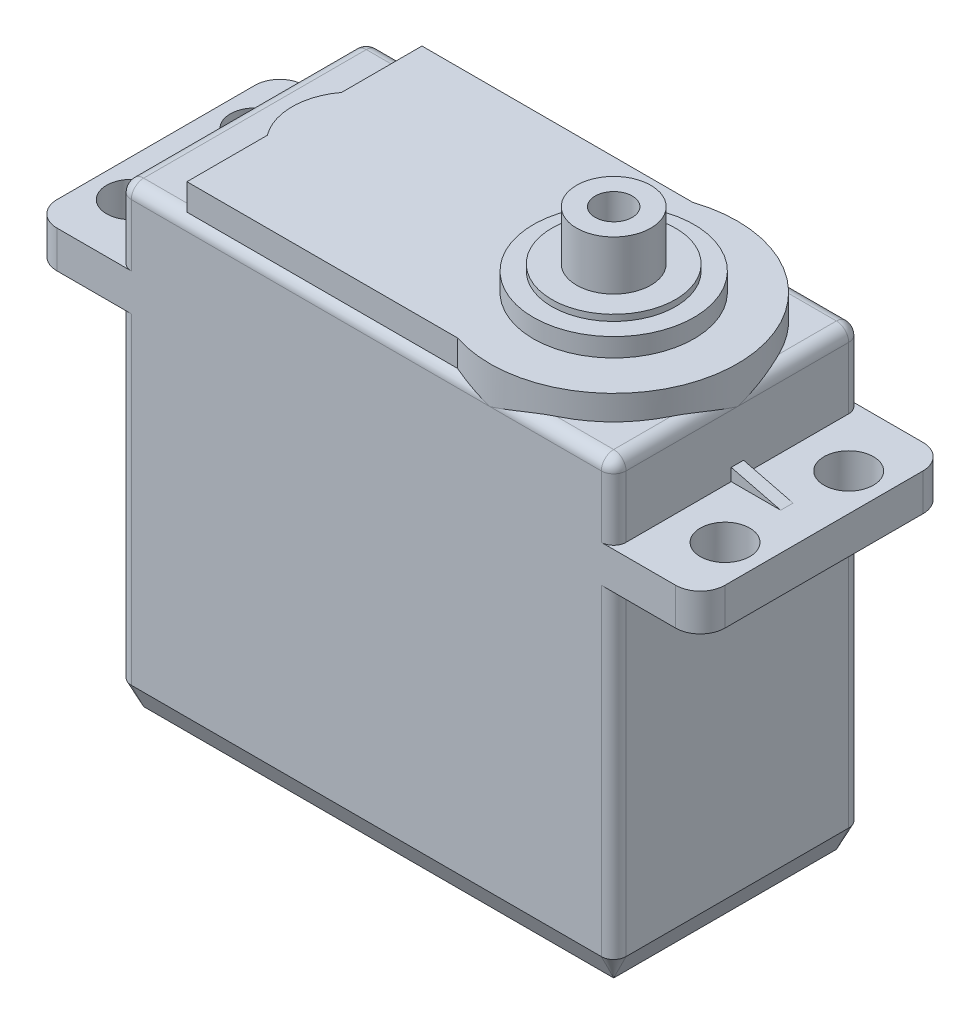
SolidWorks part; units mm, degrees
ref_plane "前视基准面" through (0, 0, 0) normal (0, 0, 1) x (1, 0, 0)
ref_plane "上视基准面" through (0, 0, 0) normal (0, 1, 0) x (1, 0, 0)
ref_plane "右视基准面" through (0, 0, 0) normal (1, 0, 0) x (0, 0, -1)
sketch "草图1" plane through (0, 0, 0) normal (0, 1, 0) x (1, 0, 0)
  line L1 (-27, 10) -> (27, 10)
  line L2 (-27, 10) -> (-27, -10)
  line L3 (-27, -10) -> (27, -10)
  line L4 (27, 10) -> (27, -10)
  line L5 (-27, 10) -> (27, -10) construction
  line L6 (-27, -10) -> (27, 10) construction
  point P0 (0, 0)
  dimension "D1" = 54
  dimension "D2" = 20
extrude "凸台-拉伸1" add sketch "草图1" along normal blind 37
sketch "草图2" plane through (0, 0, 0) normal (0, -1, 0) x (1, 0, 0)
  line L1 (-20, 10) -> (20, 10)
  line L2 (-20, 10) -> (-20, -10)
  line L3 (-20, -10) -> (20, -10)
  line L4 (20, 10) -> (20, -10)
  line L5 (-20, 10) -> (20, -10) construction
  line L6 (-20, -10) -> (20, 10) construction
  line L7 (-33.9613, 19.7038) -> (33.9613, 19.7038)
  line L8 (-33.9613, 19.7038) -> (-33.9613, -19.7038)
  line L9 (-33.9613, -19.7038) -> (33.9613, -19.7038)
  line L10 (33.9613, 19.7038) -> (33.9613, -19.7038)
  line L11 (-33.9613, 19.7038) -> (33.9613, -19.7038) construction
  line L12 (-33.9613, -19.7038) -> (33.9613, 19.7038) construction
  point P0 (0, 0)
  point P6 (0, 0)
  dimension "D1" = 40
  dimension "D2" = 20
extrude "切除-拉伸1" cut sketch "草图2" against normal blind 28
sketch "草图3" plane through (0, 37, 0) normal (0, 1, 0) x (1, 0, 0)
  line L1 (-20, 10) -> (20, 10)
  line L2 (-20, 10) -> (-20, -10)
  line L3 (-20, -10) -> (20, -10)
  line L4 (20, 10) -> (20, -10)
  line L5 (-20, 10) -> (20, -10) construction
  line L6 (-20, -10) -> (20, 10) construction
  line L7 (-33.9613, 16.6929) -> (33.9613, 16.6929)
  line L8 (-33.9613, 16.6929) -> (-33.9613, -16.6929)
  line L9 (-33.9613, -16.6929) -> (33.9613, -16.6929)
  line L10 (33.9613, 16.6929) -> (33.9613, -16.6929)
  line L11 (-33.9613, 16.6929) -> (33.9613, -16.6929) construction
  line L12 (-33.9613, -16.6929) -> (33.9613, 16.6929) construction
  point P0 (0, 0)
  point P6 (0, 0)
  dimension "D1" = 40
  dimension "D2" = 20
extrude "切除-拉伸2" cut sketch "草图3" against normal blind 6
fillet "圆角1" radius 1 12 edges at (20, 34, 10) (20, 34, -10) (-20, 34, 10) (-20, 34, -10) (-20, 14, -10) (20, 14, -10) (20, 14, 10) (-20, 14, 10) (20, 37, 0) (0, 37, -10) (-20, 37, 0) (0, 37, 10)
fillet "圆角2" radius 2 4 edges at (-27, 29.5, -10) (27, 29.5, -10) (-27, 29.5, 10) (27, 29.5, 10)
chamfer "倒角1" distance 1 distance2 2 8 edges at (0, 0, -10) (-19.7071, 0, -9.7071) (19.7071, 0, -9.7071) (-20, 0, 0) (20, 0, 0) (-19.7071, 0, 9.7071) (19.7071, 0, 9.7071) (0, 0, 10)
sketch "草图4" plane through (0, 37, 0) normal (0, 1, 0) x (1, 0, 0)
  line L0 (-36.3246, 0) -> (42.4452, 0) construction
  line L1 (0, 18.5837) -> (0, -20.5352) construction
  circle A0 centre (-24, 5) radius 2
  circle A1 centre (-24, -5) radius 2
  circle A2 centre (24, -5) radius 2
  circle A3 centre (24, 5) radius 2
  dimension "D4" = 4
  dimension "D5" = 4
  dimension "D1" = 5
  dimension "D2" = 5
  dimension "D3" = 24
extrude "切除-拉伸3" cut sketch "草图4" against normal blind 30
sketch "草图5" plane through (0, 0, 0) normal (0, 0, 1) x (1, 0, 0)
  line L0 (-20, 32) -> (-24, 31)
  line L1 (-20, 31) -> (-20, 36) construction
  line L2 (-25, 31) -> (-19, 31) construction
  dimension "D1" = 1
  dimension "D2" = 4
rib "筋1" sketch "草图5" sketch "草图5" thickness 1 extrusion direction parallel to sketch draft on no parameters "D1"=1
mirror "镜向1" about plane through (0, 0, 0) normal (1, 0, 0) of "筋1"
sketch "草图6" plane through (0, 37, 0) normal (0, 1, 0) x (1, 0, 0)
  point P2 (0, 0)
sketch "草图8" plane through (0, 37, 0) normal (0, 1, 0) x (1, 0, 0)
  line L0 (27, -8) -> (27, 8) construction
  line L1 (-15, 9.5) -> (6.8775, 9.5)
  line L2 (-15, 9.5) -> (-15, 3)
  line L3 (-15, -9.5) -> (6.8775, -9.5)
  line L4 (-15, -3) -> (-15, -9.5)
  line L5 (-15, 9.5) -> (15, -9.5) construction
  line L6 (-15, -9.5) -> (15, 9.5) construction
  arc A0 (6.8775, -9.5) -> (6.8775, 9.5) centre (10, 0) ccw
  arc A1 (-15, 3) -> (-15, -3) centre (-11, 0) ccw
  point P2 (0, 0)
  dimension "D2" = 20
  dimension "D1" = 17
  dimension "D3" = 19
  dimension "D4" = 30
extrude "凸台-拉伸4" add sketch "草图8" along normal blind 2 and the other way up to next
sketch "草图9" plane through (0, 39, 0) normal (0, 1, 0) x (1, 0, 0)
  line L0 (27, -8) -> (27, 8) construction
  circle A0 centre (10, 0) radius 6.5
  dimension "D1" = 17
  dimension "D2" = 13
extrude "凸台-拉伸5" add sketch "草图9" along normal blind 2
sketch "草图10" plane through (0, 41, 0) normal (0, 1, 0) x (1, 0, 0)
  circle A0 centre (10, 0) radius 6.5
  circle A1 centre (10, 0) radius 5
  dimension "D1" = 13
  dimension "D2" = 10
extrude "切除-拉伸4" cut sketch "草图10" against normal blind 0.5
sketch "草图11" plane through (0, 41, 0) normal (0, 1, 0) x (1, 0, 0)
  circle A0 centre (10, 0) radius 3
  dimension "D1" = 6
extrude "凸台-拉伸6" add sketch "草图11" along normal blind 4
sketch "草图14" plane through (0, 45, 0) normal (0, 1, 0) x (1, 0, 0)
  circle A0 centre (10, 0) radius 1.5
  dimension "D1" = 3
extrude "切除-拉伸5" cut sketch "草图14" against normal blind 4
